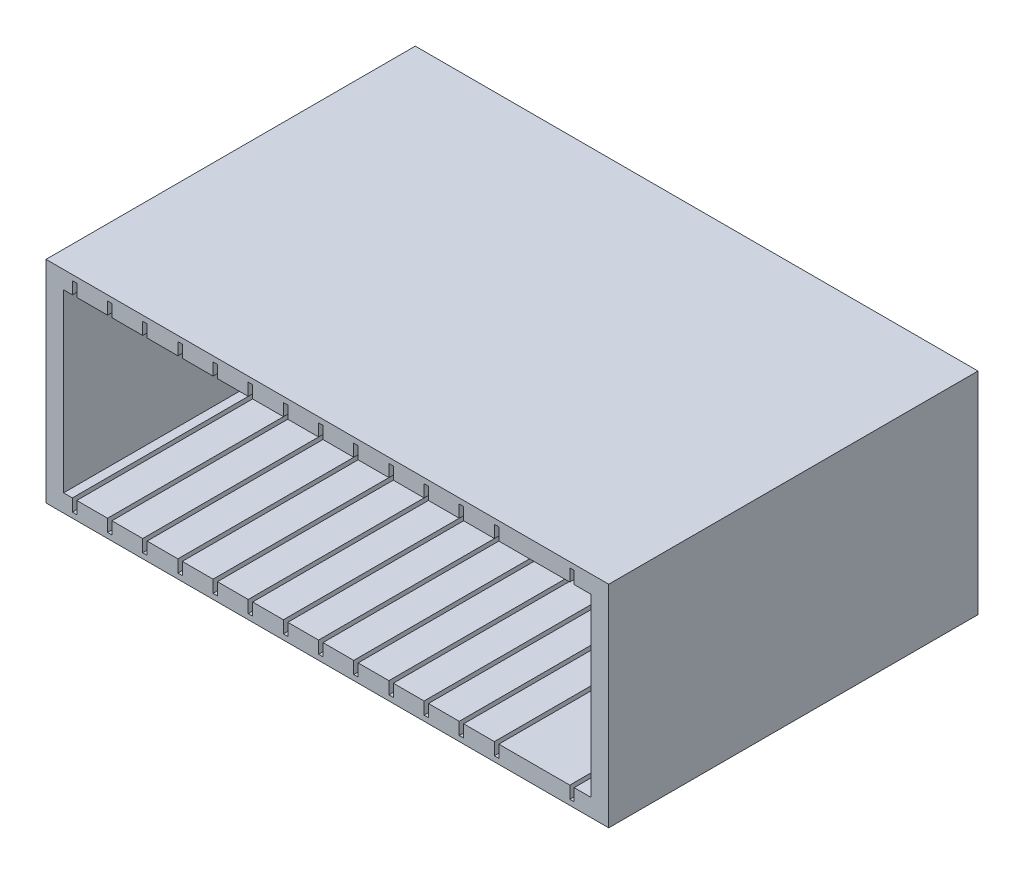
SolidWorks part; units mm, degrees
material "ABS"
ref_plane "Front Plane" through (0, 0, 0) normal (0, 0, 1) x (1, 0, 0)
ref_plane "Top Plane" through (0, 0, 0) normal (0, 1, 0) x (1, 0, 0)
ref_plane "Right Plane" through (0, 0, 0) normal (1, 0, 0) x (0, 0, -1)
sketch "Sketch1" plane through (0, 0, 0) normal (0, 0, 1) x (1, 0, 0)
  line L1 (101.6, -38.1) -> (-101.6, -38.1)
  line L2 (101.6, -38.1) -> (101.6, 38.1)
  line L3 (101.6, 38.1) -> (-101.6, 38.1)
  line L4 (-101.6, -38.1) -> (-101.6, 38.1)
  line L5 (101.6, -38.1) -> (-101.6, 38.1) construction
  line L6 (101.6, 38.1) -> (-101.6, -38.1) construction
  point P0 (0, 0)
  dimension "D1" = 203.2
  dimension "D2" = 76.2
extrude "Boss-Extrude1" add sketch "Sketch1" along normal blind 133.35
shell "Shell1" thickness 6.35
sketch "Sketch2" plane through (0, 0, 133.35) normal (0, 0, 1) x (1, 0, 0)
  line L0 (-95.25, 31.75) -> (-95.25, -31.75) construction
  line L1 (-92.075, 36.195) -> (-90.4875, 36.195)
  line L2 (-92.075, 36.195) -> (-92.075, -36.195)
  line L3 (-92.075, -36.195) -> (-90.4875, -36.195)
  line L4 (-90.4875, 36.195) -> (-90.4875, -36.195)
  line L5 (-92.075, 36.195) -> (-90.4875, -36.195) construction
  line L6 (-92.075, -36.195) -> (-90.4875, 36.195) construction
  point P0 (-91.2813, 0)
  point P5 (0, 0)
  point P7 (-83.4267, 0)
  dimension "D1" = 72.39
  dimension "D2" = 1.5875
  dimension "D3" = 3.175
extrude "Cut-Extrude1" cut sketch "Sketch2" against normal up to surface (127 mm away) up to face at (0, 0, 6.35)
pattern_linear "LPattern1" count 13 spacing 12.7 along (1, 0, 0) of "Cut-Extrude1"
sketch "Sketch3" plane through (0, 0, 133.35) normal (0, 0, 1) x (1, 0, 0)
  line L0 (61.9125, 36.195) -> (60.325, 36.195) construction
  line L1 (87.5436, 36.195) -> (89.1311, 36.195)
  line L2 (87.5436, 36.195) -> (87.5436, -36.195)
  line L3 (87.5436, -36.195) -> (89.1311, -36.195)
  line L4 (89.1311, 36.195) -> (89.1311, -36.195)
  line L5 (87.5436, 36.195) -> (89.1311, -36.195) construction
  line L6 (87.5436, -36.195) -> (89.1311, 36.195) construction
  line L7 (61.9125, -36.195) -> (60.325, -36.195) construction
  line L8 (85.725, -984.996) -> (85.725, 49015.004) construction
  line L9 (60.325, 36.195) -> (60.325, 31.75) construction
  point P0 (88.3374, 0)
  dimension "D1" = 1.8186
  dimension "D2" = 25.4
extrude "Cut-Extrude2" cut sketch "Sketch3" against normal up to surface (127 mm away)
